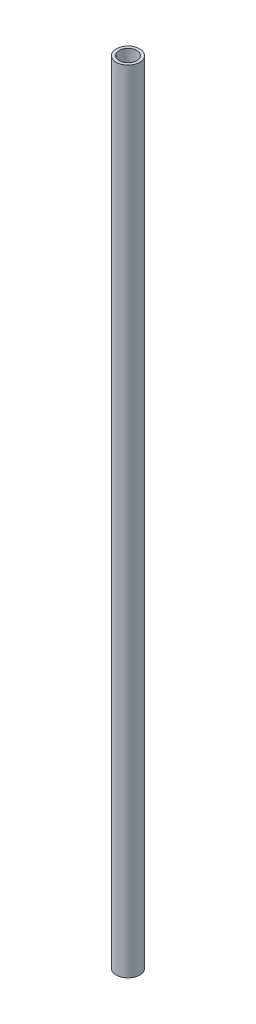
SolidWorks part; units mm, degrees
ref_plane "Front Plane" through (0, 0, 0) normal (0, 0, 1) x (1, 0, 0)
ref_plane "Top Plane" through (0, 0, 0) normal (0, 1, 0) x (1, 0, 0)
ref_plane "Right Plane" through (0, 0, 0) normal (1, 0, 0) x (0, 0, -1)
sketch "Sketch1" plane through (0, 0, 0) normal (0, 0, 1) x (1, 0, 0)
  line L0 (0, 0) -> (0, 270)
  point P6 (0, 270)
  dimension "D1" = 270
sketch "Sketch2" plane through (0, 0, 0) normal (0, 1, 0) x (1, 0, 0)
  circle A0 centre (0, 0) radius 4
  circle A1 centre (0, 0) radius 3
  dimension "D1" = 6
  dimension "D2" = 8
sweep "Sweep1" add profiles "Sketch2" path "Sketch1"
